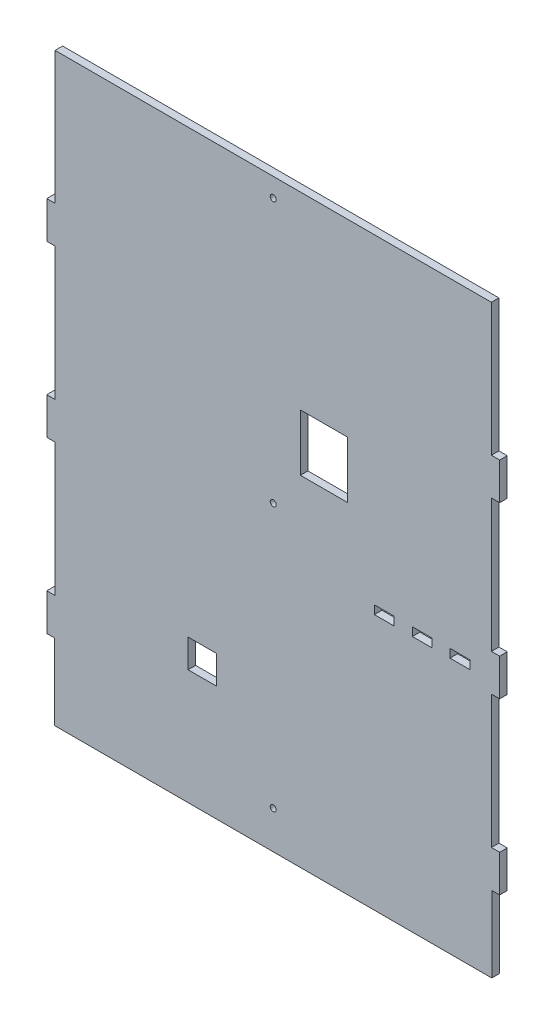
SolidWorks part; units mm, degrees
ref_plane "Front Plane" through (0, 0, 0) normal (0, 0, 1) x (1, 0, 0)
ref_plane "Top Plane" through (0, 0, 0) normal (0, 1, 0) x (1, 0, 0)
ref_plane "Right Plane" through (0, 0, 0) normal (1, 0, 0) x (0, 0, -1)
sketch "Sketch1" plane through (0, 0, 0) normal (0, 0, 1) x (1, 0, 0)
  line L1 (-130.9091, 180) -> (109.0909, 180)
  line L2 (-130.9091, 180) -> (-130.9091, -150)
  line L3 (-130.9091, -150) -> (109.0909, -150)
  line L4 (109.0909, 180) -> (109.0909, -150)
  line L5 (-130.9091, 180) -> (109.0909, -150) construction
  line L6 (-130.9091, -150) -> (109.0909, 180) construction
  point P0 (0, 0)
  dimension "D1" = 240
extrude "Boss-Extrude1" add sketch "Sketch1" along normal blind 4
sketch "Sketch2" plane through (0, 0, 0) normal (0, 0, -1) x (-1, 0, 0)
  line L0 (130.9091, 180) -> (130.9091, -150) construction
  line L1 (126.5091, 160.2) -> (130.9091, 160.2)
  line L2 (126.5091, 160.2) -> (126.5091, 89.8)
  line L3 (126.5091, 89.8) -> (130.9091, 89.8)
  line L4 (130.9091, 160.2) -> (130.9091, 89.8)
  line L5 (126.7091, -110) -> (130.7091, -110) construction
  line L6 (126.5091, 70.2) -> (130.9091, 70.2)
  line L7 (126.5091, 70.2) -> (126.5091, -0.2)
  line L8 (126.5091, -0.2) -> (130.9091, -0.2)
  line L9 (130.9091, 70.2) -> (130.9091, -0.2)
  line L10 (126.5091, -19.8) -> (130.9091, -19.8)
  line L11 (126.5091, -19.8) -> (126.5091, -90.2)
  line L12 (126.5091, -90.2) -> (130.9091, -90.2)
  line L13 (130.9091, -19.8) -> (130.9091, -90.2)
  line L14 (126.7091, -109.8) -> (130.9091, -109.8)
  line L15 (126.7091, -109.8) -> (126.7091, -150)
  line L16 (126.7091, -150) -> (130.9091, -150)
  line L17 (130.9091, -109.8) -> (130.9091, -150)
  line L18 (126.7091, -90) -> (130.7091, -90) construction
  line L19 (126.7091, -90) -> (126.7091, -20) construction
  line L20 (126.7091, -20) -> (130.7091, -20) construction
  line L21 (126.7091, 0) -> (130.7091, 0) construction
  line L22 (126.7091, 0) -> (126.7091, 70) construction
  line L23 (126.7091, 70) -> (130.7091, 70) construction
  line L24 (126.7091, 90) -> (130.7091, 90) construction
  line L25 (126.7091, 90) -> (126.7091, 160) construction
  line L26 (126.7091, 160) -> (130.7091, 160) construction
  line L27 (10.9091, 180) -> (10.9091, -150) construction
  line L28 (-109.0909, 180) -> (130.9091, 180) construction
  line L29 (130.9091, -150) -> (-109.0909, -150) construction
  line L30 (-109.0909, -109.8) -> (-109.0909, -150)
  line L31 (-104.8909, -150) -> (-109.0909, -150)
  line L32 (-104.8909, -109.8) -> (-104.8909, -150)
  line L33 (-104.8909, -109.8) -> (-109.0909, -109.8)
  line L34 (-109.0909, -19.8) -> (-109.0909, -90.2)
  line L35 (-104.6909, -90.2) -> (-109.0909, -90.2)
  line L36 (-104.6909, -19.8) -> (-104.6909, -90.2)
  line L37 (-104.6909, -19.8) -> (-109.0909, -19.8)
  line L38 (-109.0909, 70.2) -> (-109.0909, -0.2)
  line L39 (-104.6909, -0.2) -> (-109.0909, -0.2)
  line L40 (-104.6909, 70.2) -> (-104.6909, -0.2)
  line L41 (-104.6909, 70.2) -> (-109.0909, 70.2)
  line L42 (-109.0909, 160.2) -> (-109.0909, 89.8)
  line L43 (-104.6909, 89.8) -> (-109.0909, 89.8)
  line L44 (-104.6909, 160.2) -> (-104.6909, 89.8)
  line L45 (-104.6909, 160.2) -> (-109.0909, 160.2)
  dimension "D1" = 4.2
  dimension "D2" = 0.2
  dimension "D3" = 0.2
  dimension "D4" = 0.2
  dimension "D5" = 0.2
  dimension "D6" = 0.2
  dimension "D7" = 0.2
  dimension "D8" = 0.2
  dimension "D9" = 0.2
  dimension "D10" = 0.2
  dimension "D11" = 0.2
extrude "Cut-Extrude1" cut sketch "Sketch2" against normal through all
sketch "Sketch3" plane through (0, 0, 0) normal (0, 0, -1) x (-1, 0, 0)
  line L0 (126.5091, -19.8) -> (126.5091, -90.2) construction
  line L1 (41.0091, -74) -> (56.0091, -74)
  line L2 (41.0091, -74) -> (41.0091, -89)
  line L3 (41.0091, -89) -> (56.0091, -89)
  line L4 (56.0091, -74) -> (56.0091, -89)
  line L5 (126.7091, -150) -> (-104.8909, -150) construction
  point P7 (126.5091, -55)
  dimension "D1" = 15
  dimension "D2" = 15
  dimension "D3" = 70.5
  dimension "D4" = 61
extrude "Cut-Extrude2" cut sketch "Sketch3" against normal through all
sketch "Sketch4" plane through (0, 0, 4) normal (0, 0, 1) x (1, 0, 0)
  line L1 (109.0909, 180) -> (-130.9091, 180) construction
  circle A1 centre (-10.9091, 150) radius 1.6
  circle A2 centre (-10.9091, 10) radius 1.6
  circle A3 centre (-10.9091, -130) radius 1.6
  point P4 (-10.9091, 180)
  dimension "D2" = 3.2
  dimension "D1" = 30
  dimension "D3" = 3
extrude "Cut-Extrude3" cut sketch "Sketch4" against normal through all
sketch "Sketch7" plane through (0, 0, 4) normal (0, 0, 1) x (1, 0, 0)
  line L0 (109.0909, 160.2) -> (109.0909, 180) construction
  line L1 (-130.9091, 180) -> (109.0909, 180)
  line L2 (-130.9091, 180) -> (-130.9091, 160)
  line L3 (-130.9091, 160) -> (109.0909, 160)
  line L4 (109.0909, 180) -> (109.0909, 160)
  dimension "D1" = 20
extrude "Cut-Extrude6" cut sketch "Sketch7" against normal through all
sketch "Sketch12" plane through (0, 0, 0) normal (0, 0, -1) x (-1, 0, 0)
  line L1 (-53.1988, -9.8328) -> (-42.6988, -9.8328)
  line L2 (-53.1988, -9.8328) -> (-53.1988, -14.3328)
  line L3 (-53.1988, -14.3328) -> (-42.6988, -14.3328)
  line L4 (-42.6988, -9.8328) -> (-42.6988, -14.3328)
  line L5 (-73.2976, -9.8328) -> (-62.7976, -9.8328)
  line L6 (-73.2976, -9.8328) -> (-73.2976, -14.3328)
  line L7 (-73.2976, -14.3328) -> (-62.7976, -14.3328)
  line L8 (-62.7976, -9.8328) -> (-62.7976, -14.3328)
  line L9 (-93.2306, -9.7807) -> (-82.7306, -9.7807)
  line L10 (-93.2306, -9.7807) -> (-93.2306, -14.2807)
  line L11 (-93.2306, -14.2807) -> (-82.7306, -14.2807)
  line L12 (-82.7306, -9.7807) -> (-82.7306, -14.2807)
  dimension "D1" = 10.5
  dimension "D2" = 4.5
  dimension "D3" = 10.5
  dimension "D4" = 4.5
  dimension "D5" = 10.5
  dimension "D6" = 4.5
extrude "Cut-Extrude7" cut sketch "Sketch12" against normal through all
sketch "Sketch15" plane through (0, 0, 0) normal (0, 0, -1) x (-1, 0, 0)
  line L0 (-64.0909, 110) -> (85.9091, 110) construction
  line L1 (126.5091, 160) -> (-104.6909, 160) construction
  text T0 "    Fred \r\nFlintstone" font "Harlow Solid Italic" height in points 72
  point P3 (10.9091, 110)
  point P6 (10.9091, 160)
  dimension "D1" = 50
  dimension "D2" = 150
extrude "Boss-Extrude3" add sketch "Sketch15" along normal blind 3
sketch "Sketch16" plane through (0, 0, 4) normal (0, 0, 1) x (1, 0, 0)
  line L0 (-126.5091, 160) -> (104.6909, 160) construction
  line L1 (3.4909, 60) -> (28.4909, 60)
  line L2 (3.4909, 60) -> (3.4909, 30)
  line L3 (3.4909, 30) -> (28.4909, 30)
  line L4 (28.4909, 60) -> (28.4909, 30)
  line L5 (3.4909, 60) -> (28.4909, 30) construction
  line L6 (3.4909, 30) -> (28.4909, 60) construction
  line L7 (-126.5091, 160) -> (-126.5091, 89.8) construction
  point P0 (15.9909, 45)
  dimension "D1" = 30
  dimension "D2" = 25
  dimension "D3" = 100
  dimension "D4" = 130
extrude "Cut-Extrude8" cut sketch "Sketch16" against normal through all
